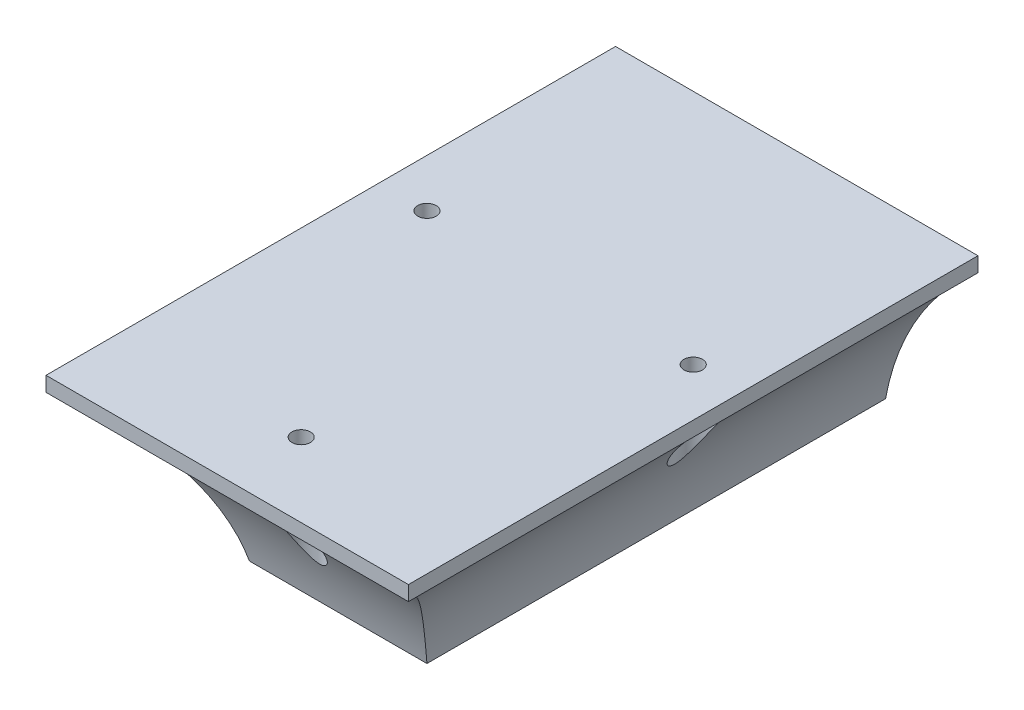
SolidWorks part; units mm, degrees
ref_plane "Front Plane" through (0, 0, 0) normal (0, 0, 1) x (1, 0, 0)
ref_plane "Top Plane" through (0, 0, 0) normal (0, 1, 0) x (1, 0, 0)
ref_plane "Right Plane" through (0, 0, 0) normal (1, 0, 0) x (0, 0, -1)
sketch "Sketch1" plane through (0, 0, 0) normal (0, 0, 1) x (1, 0, 0)
  line L0 (12.7, 12.7) -> (-12.7, 12.7)
  line L1 (-12.7, 12.7) -> (-12.7, 3.175)
  line L2 (-12.7, 3.175) -> (-10.414, 3.175)
  line L3 (-10.414, 3.175) -> (-10.414, 5.1485)
  line L4 (-9.4213, 5.6731) -> (-4.826, 2.54)
  line L5 (-4.826, 2.54) -> (-4.826, -2.54)
  line L6 (-4.826, -2.54) -> (-9.4213, -5.6731)
  line L7 (-10.414, -5.1485) -> (-10.414, -3.175)
  line L8 (-10.414, -3.175) -> (-12.7, -3.175)
  line L9 (-12.7, -3.175) -> (-12.7, -12.7)
  line L10 (-12.7, -12.7) -> (-8.89, -12.7)
  line L11 (22.3999, 0) -> (-22.3999, 0) construction
  line L12 (15.24, 15.24) -> (-15.24, 15.24)
  line L13 (-15.24, 15.24) -> (-15.24, -13.97)
  line L14 (-15.24, -13.97) -> (-8.89, -13.97)
  line L15 (-8.89, -13.97) -> (-8.89, -12.7)
  line L16 (0, 0) -> (0, 4.6071) construction
  line L17 (8.89, -13.97) -> (8.89, -12.7)
  line L18 (15.24, -13.97) -> (8.89, -13.97)
  line L19 (15.24, 15.24) -> (15.24, -13.97)
  line L20 (12.7, -12.7) -> (8.89, -12.7)
  line L21 (12.7, -3.175) -> (12.7, -12.7)
  line L22 (10.414, -3.175) -> (12.7, -3.175)
  line L23 (10.414, -5.1485) -> (10.414, -3.175)
  line L24 (4.826, -2.54) -> (9.4213, -5.6731)
  line L25 (4.826, 2.54) -> (4.826, -2.54)
  line L26 (9.4213, 5.6731) -> (4.826, 2.54)
  line L27 (10.414, 3.175) -> (10.414, 5.1485)
  line L28 (12.7, 3.175) -> (10.414, 3.175)
  line L29 (12.7, 12.7) -> (12.7, 3.175)
  arc A0 (-9.4213, -5.6731) -> (-10.414, -5.1485) centre (-9.779, -5.1485) cw
  arc A1 (-10.414, 5.1485) -> (-9.4213, 5.6731) centre (-9.779, 5.1485) cw
  arc A2 (10.414, 5.1485) -> (9.4213, 5.6731) centre (9.779, 5.1485) ccw
  arc A3 (9.4213, -5.6731) -> (10.414, -5.1485) centre (9.779, -5.1485) ccw
  point P0 (10.414, 6.35)
  point P21 (-10.414, -6.35)
  point P24 (-10.414, 6.35)
  point P37 (0, 15.24)
  point P45 (0, 12.7)
  point P46 (10.414, -6.35)
  dimension "D8" = 0.635
  dimension "D1" = 12.7
  dimension "D2" = 12.7
  dimension "D3" = 6.35
  dimension "D4" = 5.08
  dimension "D5" = 12.7
  dimension "D6" = 5.588
  dimension "D7" = 2.286
  dimension "D9" = 1.27
  dimension "D10" = 2.54
  dimension "D11" = 2.54
  dimension "D12" = 6.35
extrude "Boss-Extrude1" add sketch "Sketch1" along normal mid plane 76.2
sketch "Sketch6" plane through (0, 0, -38.1) normal (0, 0, -1) x (-1, 0, 0)
  line L0 (0, 0) -> (0, 15.9945) construction
  line L1 (-15.24, 15.24) -> (-31.115, 15.24)
  line L2 (-15.24, 15.24) -> (-15.24, -13.97)
  line L3 (15.24, 15.24) -> (31.115, 15.24)
  line L4 (-31.115, 15.24) -> (-31.115, 12.7)
  line L5 (31.115, 15.24) -> (31.115, 12.7)
  line L6 (15.24, 15.24) -> (15.24, -13.97)
  arc A0 (-31.115, 12.7) -> (-15.24, -13.97) centre (-58.9697, -21.9399) cw
  arc A1 (31.115, 12.7) -> (15.24, -13.97) centre (58.9697, -21.9399) ccw
  dimension "D2" = 44.45
  dimension "D1" = 15.875
  dimension "D3" = 2.54
extrude "Boss-Extrude3" add sketch "Sketch6" against normal up to surface (76.2 mm away) up to face at (0, -1.5875, 38.1)
sketch "Sketch3" plane through (0, 0, 0) normal (1, 0, 0) x (0, 0, -1)
  line L0 (-38.1, 12.7) -> (-38.1, -13.97) construction
  line L5 (38.1, 0.635) -> (-70.7426, 0.635) construction
  line L11 (-59.69, 15.24) -> (-59.69, 12.7)
  line L12 (-38.1, 15.24) -> (-59.69, 15.24)
  line L13 (-38.1, -13.97) -> (-40.64, -13.97)
  line L14 (-38.1, 15.24) -> (-38.1, -13.97)
  line L15 (-38.1, 15.24) -> (38.1, 15.24) construction
  line L16 (38.1, 15.24) -> (38.1, -13.97) construction
  arc A1 (-59.69, 12.7) -> (-40.64, -13.97) centre (-83.7876, -24.6511) cw
  point P2 (38.1, 0.635)
  dimension "D1" = 44.45
  dimension "D2" = 2.54
  dimension "D4" = 21.59
  dimension "D5" = 21.59
  dimension "D7" = 2.54
  dimension "D12" = 29.21
extrude "Boss-Extrude2" add sketch "Sketch3" along normal up to surface and the other way up to surface contours L12 L11 A1 L13 L14 up to face at (21.9758, 0.0803, 0) other way up to face at (-21.9758, 0.0803, 0)
sketch "Sketch7" plane through (0, 0, 38.1) normal (0, 0, -1) x (-1, 0, 0)
  line L0 (34.6086, 15.24) -> (31.115, 15.24) construction
  line L1 (31.115, 15.24) -> (31.115, 12.7) construction
  line L2 (-31.115, 12.7) -> (-31.115, 15.24) construction
  line L3 (-31.115, 15.24) -> (-34.6086, 15.24) construction
  line L4 (34.6086, 15.24) -> (31.115, 15.24)
  line L5 (31.115, 15.24) -> (31.115, 12.7)
  line L6 (-31.115, 12.7) -> (-31.115, 15.24)
  line L7 (-31.115, 15.24) -> (-34.6086, 15.24)
  arc A0 (34.6086, 15.24) -> (31.115, 12.7) centre (58.9697, -21.9399) ccw construction
  arc A1 (-31.115, 12.7) -> (-34.6086, 15.24) centre (-58.9697, -21.9399) ccw construction
  arc A2 (34.6086, 15.24) -> (31.115, 12.7) centre (58.9697, -21.9399) ccw
  arc A3 (-31.115, 12.7) -> (-34.6086, 15.24) centre (-58.9697, -21.9399) ccw
extrude "Cut-Extrude3" cut sketch "Sketch7" against normal through all
ref_plane "Plane1" through (0, 2.54, 0) normal (0, 1, 0) x (1, 0, 0)
sketch "Sketch4" plane through (0, 2.54, 0) normal (0, 1, 0) x (1, 0, 0)
  line L0 (0, 0) -> (0, -70.3147) construction
  line L1 (31.115, -59.69) -> (-31.115, -59.69) construction
  circle A0 centre (0, -46.99) radius 3.175
  dimension "D2" = 6.35
  dimension "D1" = 12.7
extrude "Cut-Extrude1" cut sketch "Sketch4" against normal up to next and the other way blind 6.35
sketch "Sketch5" plane through (0, 8.89, 0) normal (0, -1, 0) x (1, 0, 0)
  circle A0 centre (0, 46.99) radius 1.5875
  circle A1 centre (0, 46.99) radius 3.175 construction
  dimension "D1" = 3.175
extrude "Cut-Extrude2" cut sketch "Sketch5" against normal up to next
pattern_linear "LPattern1" count 2 spacing 44.45 along (0, 0, -1) count 2 spacing 22.86 along (1, 0, 0) skipping (0, 1), (1, 0) of "Cut-Extrude1", "Cut-Extrude2"
mirror "Mirror1" about plane through (0, 0, 0) normal (1, 0, 0) of "LPattern1"
